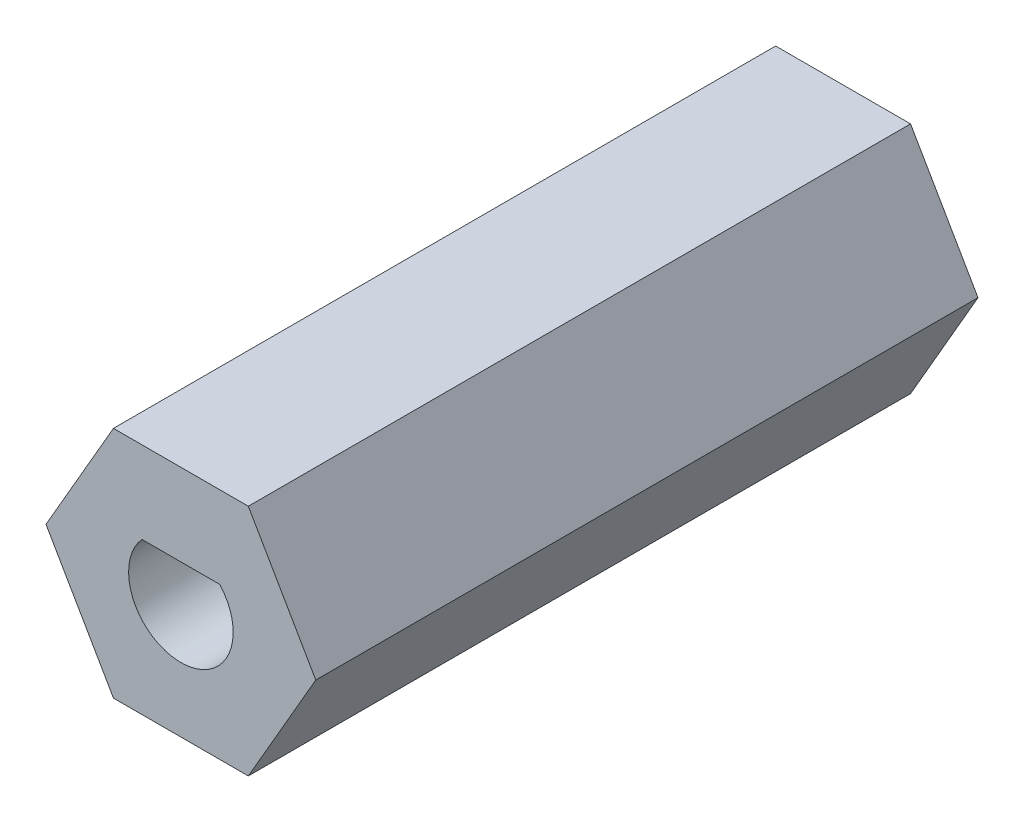
SolidWorks part; units mm, degrees
ref_plane "前视基准面" through (0, 0, 0) normal (0, 0, 1) x (1, 0, 0)
ref_plane "上视基准面" through (0, 0, 0) normal (0, 1, 0) x (1, 0, 0)
ref_plane "右视基准面" through (0, 0, 0) normal (1, 0, 0) x (0, 0, -1)
other "Configuration Table"
sketch "草图1" plane through (0, 0, 0) normal (0, 0, 1) x (1, 0, 0)
  line L0 (0, 7.0378) -> (0, -7.5289) construction
  line L1 (-6.1185, 0) -> (6.098, 0) construction
  line L2 (-1.935, 3.3515) -> (1.935, 3.3515)
  line L3 (1.935, 3.3515) -> (3.87, 0)
  line L4 (1.935, -3.3515) -> (3.87, 0)
  line L5 (-1.935, -3.3515) -> (1.935, -3.3515)
  line L6 (-1.935, -3.3515) -> (-3.87, 0)
  line L7 (-1.935, 3.3515) -> (-3.87, 0)
  point P11 (0, -3.3515)
  point P13 (0, 3.3515)
  dimension "D1" = 3.87
  dimension "D2" = 120
extrude "凸台-拉伸1" add sketch "草图1" along normal blind 19
sketch "草图2" plane through (0, 0, 19) normal (0, 0, 1) x (1, 0, 0)
  line L0 (-1.118, 1) -> (1.118, 1)
  arc A0 (-1.118, 1) -> (1.118, 1) centre (0, 0) ccw
  dimension "D1" = 3
  dimension "D2" = 1
extrude "切除-拉伸1" cut sketch "草图2" against normal blind 8
sketch "草图3" plane through (0, 0, 0) normal (0, 0, -1) x (-1, 0, 0)
  circle A0 centre (0, 0) radius 1.1
  dimension "D1" = 2.2
extrude "切除-拉伸2" cut sketch "草图3" against normal blind 8
